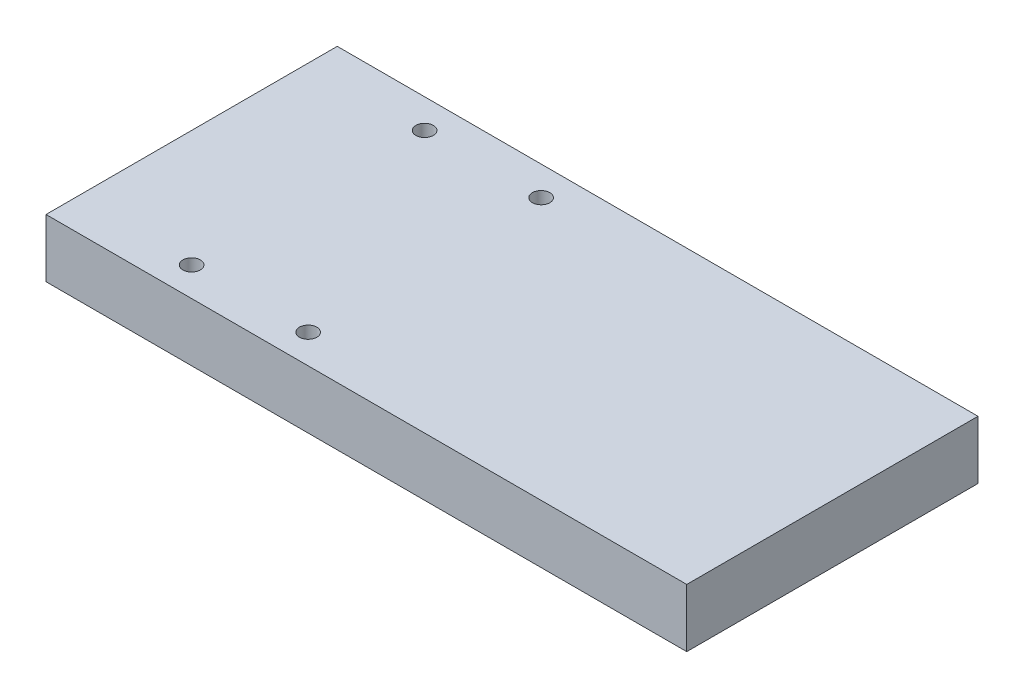
SolidWorks part; units mm, degrees
material "Сосна"
ref_plane "Спереди" through (0, 0, 0) normal (0, 0, 1) x (1, 0, 0)
ref_plane "Сверху" through (0, 0, 0) normal (0, 1, 0) x (1, 0, 0)
ref_plane "Справа" through (0, 0, 0) normal (1, 0, 0) x (0, 0, -1)
sketch "Эскиз1" plane through (0, 0, 0) normal (0, 1, 0) x (1, 0, 0)
  line L1 (0, 0) -> (220, 0)
  line L2 (0, 0) -> (0, 100)
  line L3 (0, 100) -> (220, 100)
  line L4 (220, 0) -> (220, 100)
  dimension "D1" = 220
  dimension "D2" = 100
extrude "Бобышка-Вытянуть1" add sketch "Эскиз1" along normal blind 20
sketch "Эскиз3" plane through (0, 20, 0) normal (0, 1, 0) x (1, 0, 0)
  line L0 (0, 90) -> (220, 90) construction
  line L1 (0, 100) -> (0, 0) construction
  line L2 (220, 0) -> (220, 100) construction
  line L3 (0, 10) -> (220, 10) construction
  line L4 (220, 100) -> (0, 100) construction
  line L5 (0, 0) -> (220, 0) construction
  line L6 (100, 100) -> (100, 0) construction
  circle A1 centre (40, 90) radius 3
  circle A2 centre (80, 90) radius 3
  circle A4 centre (40, 10) radius 3
  circle A5 centre (80, 10) radius 3
  dimension "D3" = 20
  dimension "D10" = 6
  dimension "D11" = 6
  dimension "D13" = 6
  dimension "D14" = 6
  dimension "D1" = 10
  dimension "D2" = 10
  dimension "D4" = 60
  dimension "D6" = 20
  dimension "D7" = 60
  dimension "D15" = 120
extrude "Вырез-Вытянуть2" cut sketch "Эскиз3" against normal blind 20
sketch "Эскиз4" plane through (0, 0, 0) normal (0, -1, 0) x (1, 0, 0)
  line L0 (220, 0) -> (220, -100) construction
  line L3 (220, -100) -> (0, -100) construction
  line L6 (0, 0) -> (220, 0) construction
  circle A0 centre (210, -10) radius 3
  circle A1 centre (110, -10) radius 3
  circle A2 centre (210, -90) radius 3
  circle A3 centre (110, -90) radius 3
  dimension "D3" = 10
  dimension "D5" = 10
  dimension "D7" = 6
  dimension "D8" = 6
  dimension "D9" = 6
  dimension "D10" = 6
  dimension "D2" = 10
  dimension "D4" = 10
